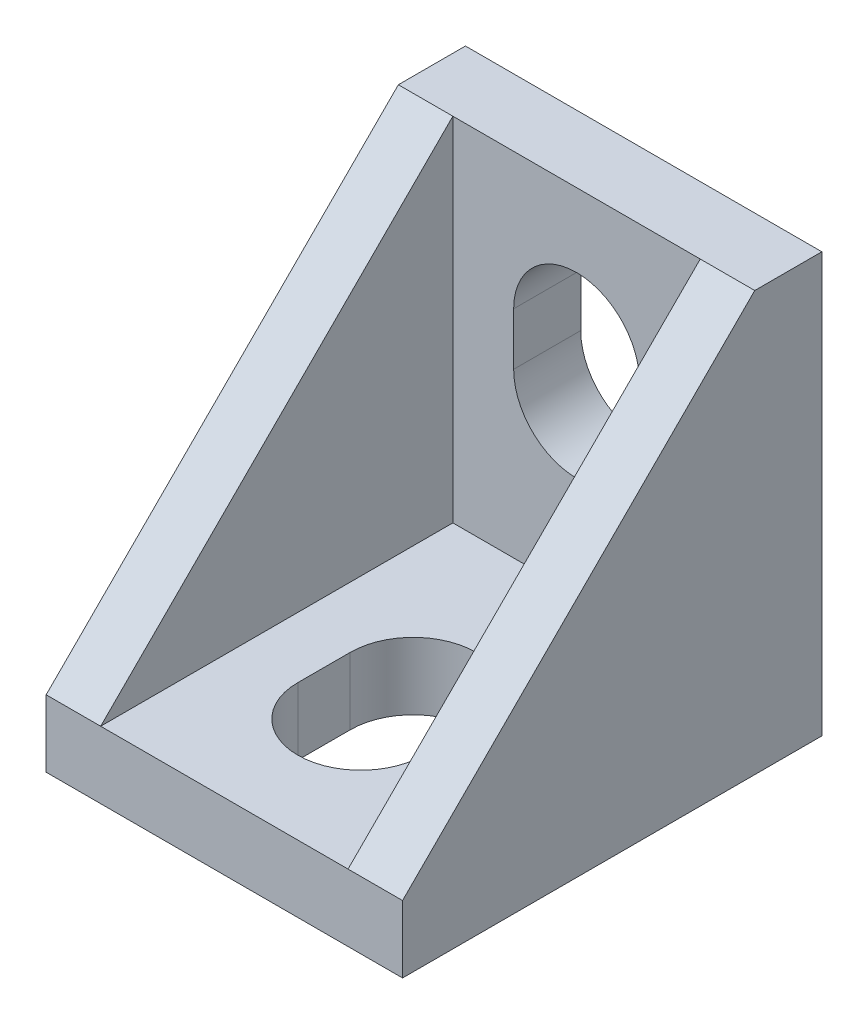
SolidWorks part; units mm, degrees
ref_plane "前视基准面" through (0, 0, 0) normal (0, 0, 1) x (1, 0, 0)
ref_plane "上视基准面" through (0, 0, 0) normal (0, 1, 0) x (1, 0, 0)
ref_plane "右视基准面" through (0, 0, 0) normal (1, 0, 0) x (0, 0, -1)
sketch "草图1" plane through (0, 0, 0) normal (0, 0, 1) x (1, 0, 0)
  line L1 (-8.5, 10) -> (8.5, 10)
  line L2 (-8.5, 10) -> (-8.5, -10)
  line L3 (-8.5, -10) -> (8.5, -10)
  line L4 (8.5, 10) -> (8.5, -10)
  line L5 (-8.5, 10) -> (8.5, -10) construction
  line L6 (-8.5, -10) -> (8.5, 10) construction
  point P0 (0, 0)
  dimension "D1" = 17
  dimension "D2" = 20
extrude "凸台-拉伸1" add sketch "草图1" along normal blind 3.2
sketch "草图2" plane through (0, 0, 3.2) normal (0, 0, 1) x (1, 0, 0)
  line L0 (8.5, -10) -> (8.5, 10) construction
  line L1 (-8.5, -10) -> (8.5, -10)
  line L2 (-8.5, -10) -> (-8.5, -6.8)
  line L3 (-8.5, -6.8) -> (8.5, -6.8)
  line L4 (8.5, -10) -> (8.5, -6.8)
  dimension "D1" = 3.2
extrude "凸台-拉伸2" add sketch "草图2" along normal blind 16.8
sketch "草图3" plane through (-8.5, 0, 0) normal (-1, 0, 0) x (0, 0, 1)
  line L0 (3.2, 10) -> (20, -6.8)
  line L1 (20, -6.8) -> (3.2, -6.8)
  line L2 (3.2, -6.8) -> (3.2, 10)
extrude "凸台-拉伸3" add sketch "草图3" against normal blind 2.6
mirror "镜向1" about plane through (0, 0, 0) normal (1, 0, 0) of "凸台-拉伸3"
sketch "草图4" plane through (0, 0, 3.2) normal (0, 0, 1) x (1, 0, 0)
  line L0 (0, 3.4951) -> (0, 0.9951) construction
  line L1 (3, 3.4951) -> (3, 0.9951)
  line L2 (-3, 3.4951) -> (-3, 0.9951)
  arc A0 (3, 3.4951) -> (-3, 3.4951) centre (0, 3.4951) ccw
  arc A1 (-3, 0.9951) -> (3, 0.9951) centre (0, 0.9951) ccw
  point P2 (0, 2.2451)
  dimension "D2" = 3
  dimension "D1" = 2.5
extrude "切除-拉伸1" cut sketch "草图4" against normal through all
ref_plane "基准面1" through (0, -5, 5) normal (0, -0.7071, 0.7071) x (1, 0, 0)
mirror "镜向2" about plane through (0, -5, 5) normal (0, -0.7071, 0.7071) of "切除-拉伸1"
